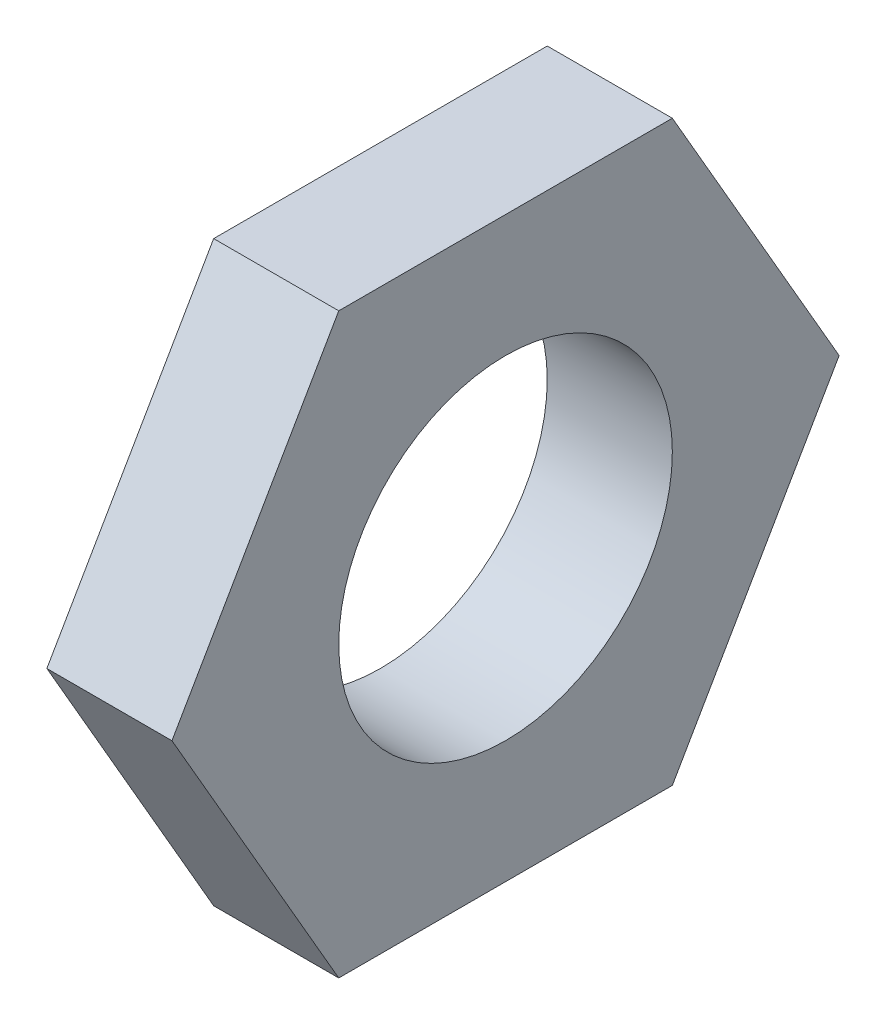
SolidWorks part; units mm, degrees
ref_plane "Alzado" through (0, 0, 0) normal (0, 0, 1) x (1, 0, 0)
ref_plane "Planta" through (0, 0, 0) normal (0, 1, 0) x (1, 0, 0)
ref_plane "Vista lateral" through (0, 0, 0) normal (1, 0, 0) x (0, 0, -1)
sketch "Croquis1" plane through (0, 0, 0) normal (1, 0, 0) x (0, 0, -1)
  line L1 (8, 0) -> (4, 6.9282)
  line L2 (4, 6.9282) -> (-4, 6.9282)
  line L3 (-4, 6.9282) -> (-8, 0)
  line L4 (-8, 0) -> (-4, -6.9282)
  line L5 (-4, -6.9282) -> (4, -6.9282)
  line L6 (4, -6.9282) -> (8, 0)
  circle A0 centre (0, 0) radius 4
  circle A1 centre (0, 0) radius 6.9282 construction
  dimension "D1" = 8
  dimension "D2" = 8
extrude "Saliente-Extruir1" add sketch "Croquis1" along normal blind 3
